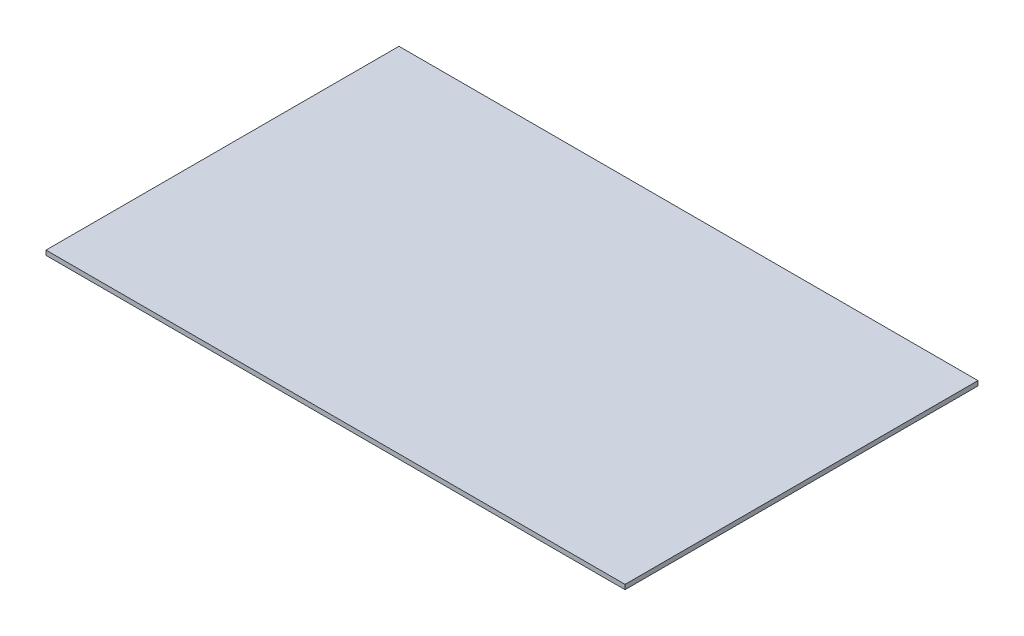
SolidWorks part; units mm, degrees
ref_plane "Front Plane" through (0, 0, 0) normal (0, 0, 1) x (1, 0, 0)
ref_plane "Top Plane" through (0, 0, 0) normal (0, 1, 0) x (1, 0, 0)
ref_plane "Right Plane" through (0, 0, 0) normal (1, 0, 0) x (0, 0, -1)
sketch "Sketch1" plane through (0, 0, 0) normal (0, 1, 0) x (1, 0, 0)
  line L1 (-135.6041, 74.5116) -> (239.4259, 74.5116)
  line L2 (-135.6041, 74.5116) -> (-135.6041, -154.1034)
  line L3 (-135.6041, -154.1034) -> (239.4259, -154.1034)
  line L4 (239.4259, 74.5116) -> (239.4259, -154.1034)
  dimension "D1" = 375.03
  dimension "D2" = 228.615
extrude "Boss-Extrude1" add sketch "Sketch1" along normal blind 3
